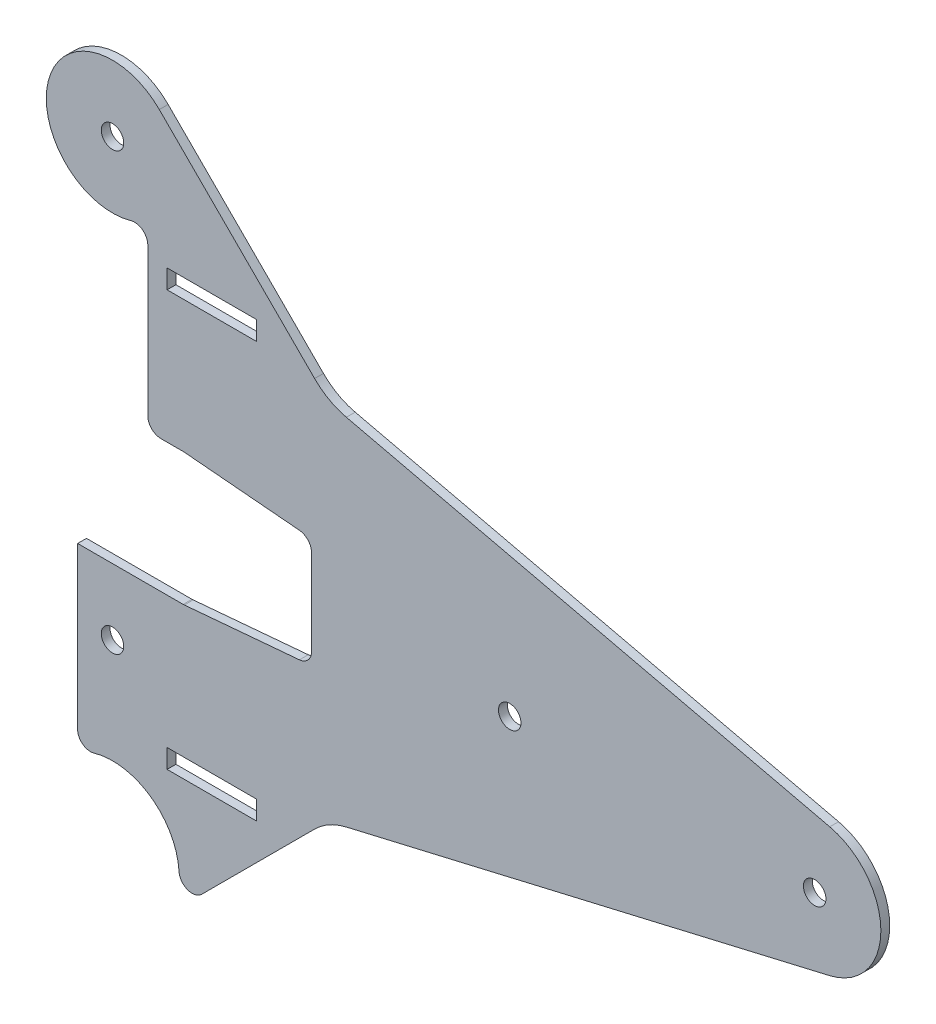
SolidWorks part; units mm, degrees
ref_plane "Front Plane" through (0, 0, 0) normal (0, 0, 1) x (1, 0, 0)
ref_plane "Top Plane" through (0, 0, 0) normal (0, 1, 0) x (1, 0, 0)
ref_plane "Right Plane" through (0, 0, 0) normal (1, 0, 0) x (0, 0, -1)
sketch "Sketch1" plane through (0, 0, 0) normal (0, 0, 1) x (1, 0, 0)
  line L0 (0, 0) -> (225, 0) construction
  line L1 (0, 0) -> (-75.9033, 0) construction
  line L2 (15, 15) -> (45, 12.375) construction
  line L3 (-45, -45) -> (45, -45) construction
  line L4 (-45, -45) -> (-45, 45) construction
  line L5 (-45, 45) -> (45, 45) construction
  line L6 (45, -45) -> (45, 45) construction
  line L7 (-45, -45) -> (45, 45) construction
  line L8 (-45, 45) -> (45, -45) construction
  line L9 (-15, -15) -> (15, -15) construction
  line L10 (-15, -15) -> (-15, 15) construction
  line L11 (-15, 15) -> (15, 15) construction
  line L12 (15, -15) -> (15, 15) construction
  line L13 (-15, -15) -> (15, 15) construction
  line L14 (-15, 15) -> (15, -15) construction
  line L15 (15, 15) -> (45, 15) construction
  line L16 (45, 45) -> (15, 15) construction
  line L17 (15, 15) -> (12.375, 45) construction
  line L18 (14.8729, 17.6) -> (12.7063, 42.3615) construction
  line L19 (17.6, 14.8729) -> (42.3615, 12.7063) construction
  line L20 (15.0923, 15.0923) -> (12.4746, 45.0087) construction
  line L21 (15.0923, 15.0923) -> (45.0087, 12.4746) construction
  line L22 (45.1, -9.7177) -> (45.1, 9.7177) construction
  line L23 (12.7063, 42.3615) -> (12.4746, 45.0087) construction
  line L24 (45.1, -45) -> (45.1, 45) construction
  line L25 (225, 53) -> (45, 53) construction
  line L26 (17.6, -14.8729) -> (42.3615, -12.7063) construction
  line L27 (14.8729, -17.6) -> (12.7063, -42.3615) construction
  line L28 (0, -45.1) -> (9.7177, -45.1) construction
  line L29 (0, 0) -> (0, 45.1) construction
  line L30 (-14.8729, 17.6) -> (-12.7063, 42.3615) construction
  line L31 (32.4746, 45) -> (162.5092, 14.6063) construction
  line L32 (-45, 49) -> (45, 49) construction
  line L33 (-12.7063, 42.3615) -> (-13.7896, 29.9807) construction
  line L34 (225, -45) -> (45, -45) construction
  line L35 (225, -45) -> (225, 45) construction
  line L36 (225, 45) -> (45, 45) construction
  line L37 (45, -45) -> (45, 45) construction
  line L38 (225, -45) -> (45, 45) construction
  line L39 (225, 45) -> (45, -45) construction
  line L40 (12.4746, 45.0087) -> (12.4746, 49) construction
  line L41 (12.4746, 49) -> (32.4746, 49) construction
  line L42 (32.4746, -49) -> (32.4746, -45) construction
  line L43 (12.4746, -49) -> (32.4746, -49) construction
  line L44 (14.8729, -17.6) -> (12.7063, -42.3615) construction
  line L45 (12.4746, -45.0087) -> (12.4746, -49) construction
  line L46 (12.7063, -42.3615) -> (12.4746, -45.0087) construction
  line L47 (32.4746, 49) -> (32.4746, 45) construction
  line L48 (32.4746, -45) -> (162.5092, -14.6063) construction
  line L49 (174.0952, 0) -> (45.1, 0) construction
  line L50 (-45, 53) -> (45, 53) construction
  line L51 (0, 0) -> (0, 90) construction
  line L52 (12.4746, 49) -> (32.4746, 49) construction
  line L53 (12.4746, 49) -> (12.4746, 45) construction
  line L54 (12.4746, 45) -> (32.4746, 45) construction
  line L55 (32.4746, 49) -> (32.4746, 45) construction
  line L56 (12.3746, 49.2) -> (32.5746, 49.2)
  line L57 (12.3746, 49.2) -> (12.3746, 44.9)
  line L58 (12.3746, 44.9) -> (32.5746, 44.9)
  line L59 (32.5746, 49.2) -> (32.5746, 44.9)
  line L60 (10.6066, 79.3934) -> (45.7949, 44.2051)
  line L61 (162.5092, 14.6063) -> (52.9874, 40.2054)
  line L62 (-15, 0) -> (-15, 90) construction
  line L63 (-12, 15) -> (16.0162, 15) construction
  line L64 (-15, 68.7868) -> (-15, 18) construction
  line L65 (16.2777, 14.9886) -> (42.3615, 12.7063)
  line L66 (45.1, 9.7177) -> (45.1, -9.7177)
  line L67 (16.2777, -14.9886) -> (42.3615, -12.7063)
  line L68 (-12, -15) -> (16.0162, -15) construction
  line L69 (-15, -68.7868) -> (-15, -18) construction
  line L70 (10.6066, -79.3934) -> (45.7949, -44.2051) construction
  line L71 (162.5092, -14.6063) -> (52.9874, -40.2054)
  line L72 (12.3746, -49.2) -> (12.3746, -44.9)
  line L73 (12.3746, -44.9) -> (32.5746, -44.9)
  line L74 (12.3746, -49.2) -> (32.5746, -49.2)
  line L75 (32.5746, -49.2) -> (32.5746, -44.9)
  line L76 (8, 0) -> (8, 8) construction
  line L77 (8, 0) -> (8, -95.7887) construction
  line L78 (8, 51.4952) -> (8, 18)
  line L79 (0, -68.7868) -> (0, 68.7868) construction
  line L80 (20.1881, -69.8119) -> (45, -45)
  line L81 (-8, -51.4952) -> (-8, -18) construction
  line L82 (-5, -15) -> (16.0162, -15) construction
  line L83 (-7.9, -51.4952) -> (-7.9, -15)
  line L84 (-7.9, -15) -> (16.0162, -15)
  line L85 (16.0162, 15) -> (11, 15)
  line L86 (8, 15) -> (8, 90) construction
  line L87 (-8, -51.4952) -> (-8, -15) construction
  line L88 (8, 0) -> (8, 90) construction
  line L89 (45.7949, -44.2051) -> (45, -45)
  line L90 (0, -53.6868) -> (0, -15) construction
  arc A0 (14.8729, 17.6) -> (17.6, 14.8729) centre (17.8615, 17.8615) ccw construction
  arc A1 (42.3615, 12.7063) -> (45.1, 9.7177) centre (42.1, 9.7177) cw
  arc A2 (162.5092, 14.6063) -> (162.5092, -14.6063) centre (159.0952, 0) cw
  arc A3 (42.3615, -12.7063) -> (45.1, -9.7177) centre (42.1, -9.7177) ccw construction
  arc A4 (14.8729, -17.6) -> (17.6, -14.8729) centre (17.8615, -17.8615) cw construction
  arc A5 (15.0723, -67.8723) -> (-4.1944, -54.2811) centre (0, -68.7868) ccw
  arc A6 (-12.7063, 42.3615) -> (-9.7177, 45.1) centre (-9.7177, 42.1) cw construction
  circle A7 centre (159.0952, 0) radius 2.55
  circle A8 centre (90, 0) radius 2.55
  arc A9 (45.7949, 44.2051) -> (52.9874, 40.2054) centre (56.4015, 54.8117) ccw
  arc A10 (-15, 68.7868) -> (10.6066, 79.3934) centre (0, 68.7868) cw
  arc A11 (16.2777, 14.9886) -> (16.0162, 15) centre (16.0162, 12) ccw
  arc A12 (-15, 18) -> (-12, 15) centre (-12, 18) ccw construction
  arc A13 (42.3615, -12.7063) -> (45.1, -9.7177) centre (42.1, -9.7177) ccw
  arc A14 (16.2777, -14.9886) -> (16.0162, -15) centre (16.0162, -12) cw
  arc A15 (-15, -18) -> (-12, -15) centre (-12, -18) cw construction
  arc A16 (-15, -68.7868) -> (10.6066, -79.3934) centre (0, -68.7868) ccw construction
  arc A17 (45.7949, -44.2051) -> (52.9874, -40.2054) centre (56.4015, -54.8117) cw
  circle A18 centre (0, 68.7868) radius 15 construction
  arc A19 (-15, 68.7868) -> (4.1667, 54.3771) centre (0, 68.7868) ccw
  arc A20 (4.1667, 54.3771) -> (8, 51.4952) centre (5, 51.4952) cw
  arc A21 (-15, -68.7868) -> (4.1667, -54.3771) centre (0, -68.7868) cw construction
  arc A22 (4.1667, -54.3771) -> (8, -51.4952) centre (5, -51.4952) ccw construction
  arc A23 (15, -68.7868) -> (-4.1667, -54.3771) centre (0, -68.7868) ccw construction
  arc A24 (-4.1667, -54.3771) -> (-8, -51.4952) centre (-5, -51.4952) cw construction
  arc A25 (14.9768, -67.9522) -> (-4.1667, -54.3771) centre (0, -68.7868) ccw construction
  arc A26 (14.9768, -67.9522) -> (20.0934, -69.9066) centre (17.9721, -67.7852) ccw construction
  circle A27 centre (0, 68.7868) radius 2.55
  arc A28 (-4.1944, -54.2811) -> (-7.9, -51.4952) centre (-5, -51.4952) cw
  arc A29 (-8, -18) -> (-5, -15) centre (-5, -18) cw construction
  arc A30 (8, 18) -> (11, 15) centre (11, 18) ccw
  circle A31 centre (0, -30) radius 2.55
  arc A32 (20.1881, -69.8119) -> (15.0723, -67.8723) centre (18.0668, -67.6906) cw
  point P28 (135, 0)
  point P33 (45.1, 0)
  point P76 (48.8206, 41.1794)
  point P85 (16.1472, 15)
  point P112 (8, 56.0982)
  point P137 (-8, -15)
  dimension "D5" = 3
  dimension "D7" = 3
  dimension "D9" = 4
  dimension "D10" = 20
  dimension "D11" = 15
  dimension "D12" = 5.1
  dimension "D13" = 90
  dimension "D20" = 15
  dimension "D19" = 15
  dimension "D23" = 3
  dimension "D24" = 3
  dimension "D26" = 3
  dimension "D27" = 3
  dimension "D29" = 3
  dimension "D30" = 3
  dimension "D31" = 5.1
  dimension "D1" = 90
  dimension "D2" = 0.1
  dimension "D3" = 30
  dimension "D4" = 2.625
  dimension "D8" = 180
  dimension "D15" = 0.2
  dimension "D16" = 0.1
  dimension "D17" = 0.1
  dimension "D18" = 0.1
  dimension "D21" = 49.7637
  dimension "D22" = 45
  dimension "D32" = 15
  dimension "D33" = 90
  dimension "D6" = 0.1
  dimension "D14" = 8
  dimension "D25" = 8
  dimension "D28" = 0.1
extrude "Boss-Extrude1" add sketch "Sketch1" along normal blind 2
